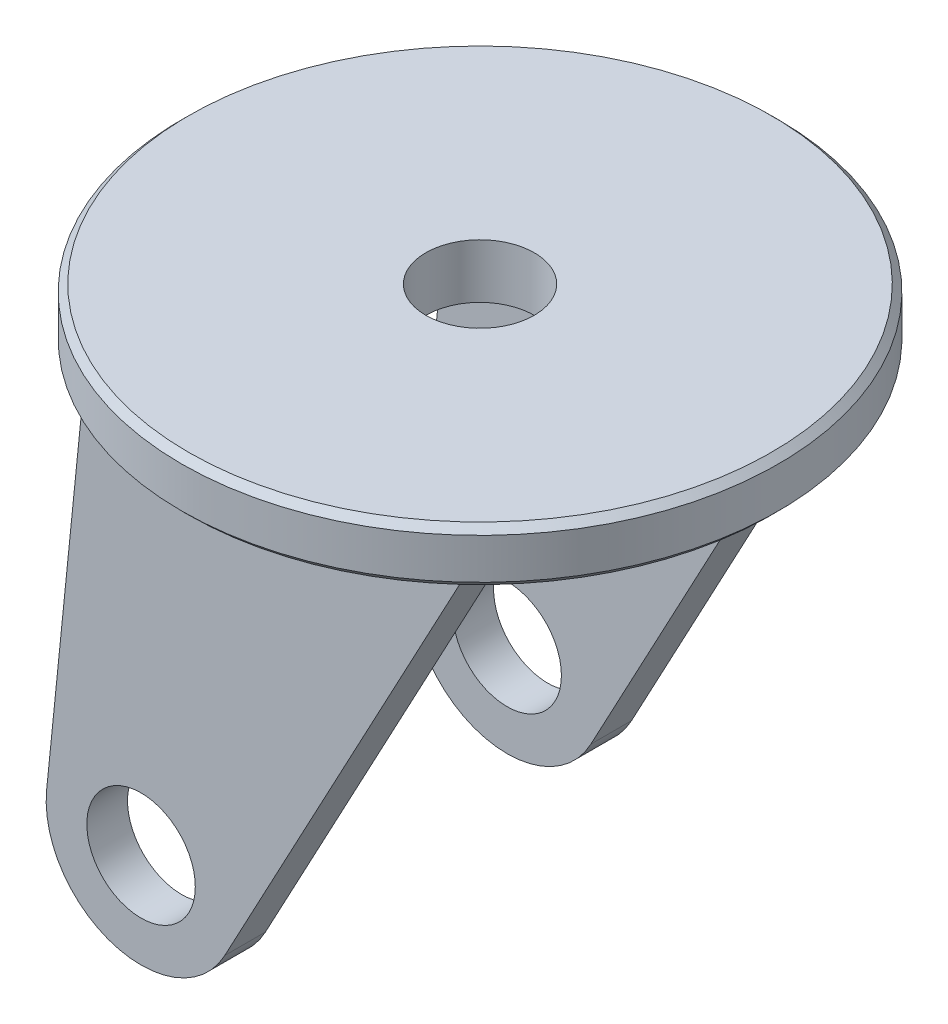
SolidWorks part; units mm, degrees
ref_plane "Front Plane" through (0, 0, 0) normal (0, 0, 1) x (1, 0, 0)
ref_plane "Top Plane" through (0, 0, 0) normal (0, 1, 0) x (1, 0, 0)
ref_plane "Right Plane" through (0, 0, 0) normal (1, 0, 0) x (0, 0, -1)
sketch "Sketch6" plane through (0, 0, 0) normal (0, 1, 0) x (1, 0, 0)
  circle A0 centre (0, 0) radius 11
  dimension "D1" = 22
extrude "Boss-Extrude3" add sketch "Sketch6" along normal blind 2
chamfer "Chamfer3" distance 0.25 angle 45 2 edges at (0, 0, 11) (0, 2, 11)
ref_plane "Plane3" through (0, 0, 6) normal (0, 0, 1) x (1, 0, 0)
sketch "Sketch7" plane through (0, 0, 6) normal (0, 0, 1) x (1, 0, 0)
  line L0 (-7, 0) -> (7, 0)
  line L1 (-10.75, 0) -> (10.75, 0) construction
  line L2 (7, 0) -> (-1.9143, -16.6519)
  line L3 (-7, 0) -> (-8.4822, -14.6476)
  arc A0 (-8.4822, -14.6476) -> (-1.9143, -16.6519) centre (-5, -15) ccw
  circle A1 centre (-5, -15) radius 2
  point P6 (0, 0)
  dimension "D2" = 7
  dimension "D1" = 14
  dimension "D3" = 15
  dimension "D4" = 12
extrude "Boss-Extrude4" add sketch "Sketch7" along normal blind 1.5
mirror "Mirror2" about plane through (0, 0, 0) normal (0, 0, 1) of "Boss-Extrude4"
sketch "Sketch8" plane through (0, 2, 0) normal (0, 1, 0) x (1, 0, 0)
  circle A0 centre (0, 0) radius 2
extrude "Cut-Extrude1" cut sketch "Sketch8" against normal through all
